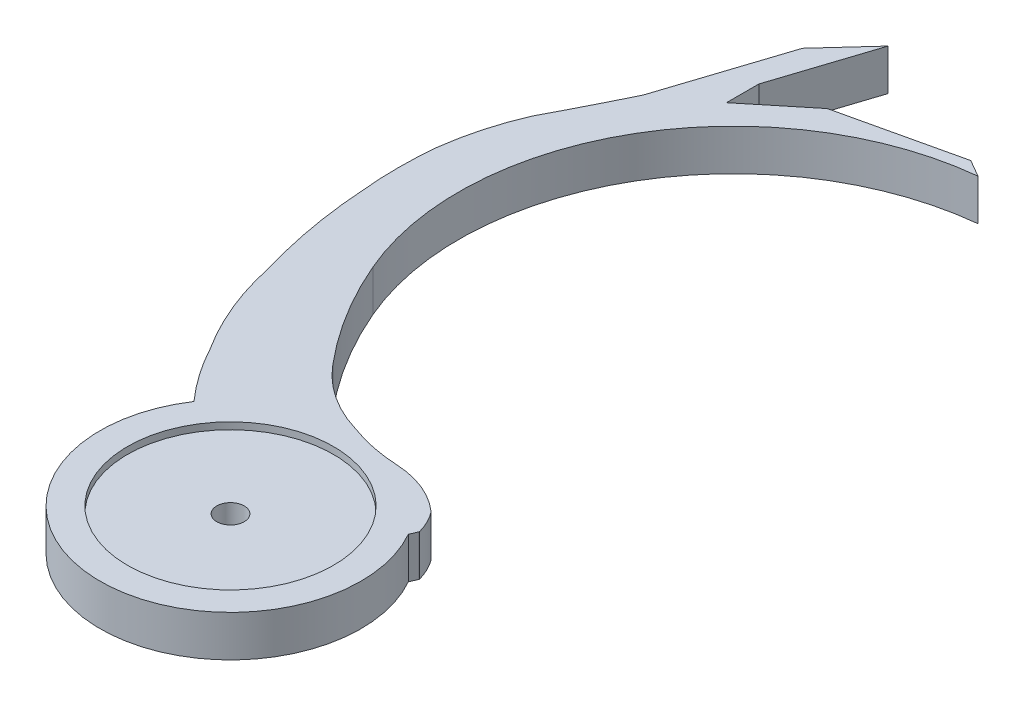
SolidWorks part; units mm, degrees
ref_plane "Front Plane" through (0, 0, 0) normal (0, 0, 1) x (1, 0, 0)
ref_plane "Top Plane" through (0, 0, 0) normal (0, 1, 0) x (1, 0, 0)
ref_plane "Right Plane" through (0, 0, 0) normal (1, 0, 0) x (0, 0, -1)
sketch "Sketch2" plane through (0, 0, 0) normal (0, 1, 0) x (1, 0, 0)
  line L0 (0, 0) -> (-35.9464, 0) construction
  line L1 (-35.9464, 0) -> (41.3976, 0) construction
  line L2 (41.3976, 0) -> (0, 0) construction
  line L3 (0, 0) -> (0, 18.7982) construction
  line L4 (0, 18.7982) -> (0, -23.465) construction
  circle A0 centre (0, 0) radius 20 construction
  circle A1 centre (0, 0) radius 23.465
sketch "Sketch4" plane through (0, 0, 0) normal (0, 1, 0) x (1, 0, 0)
  line L0 (-19.7005, -1.3216) -> (20.2972, -0.8891) construction
  circle A0 centre (0, 0) radius 23.4639 construction
  dimension "D1" = 40
sketch "Sketch5" plane through (0, 0, 0) normal (0, 1, 0) x (1, 0, 0)
  line L0 (-19.9303, -0.0851) -> (20.0695, 0.0365) construction
  dimension "D1" = 40
sketch "Sketch6" plane through (0, 0, 0) normal (0, 1, 0) x (1, 0, 0)
  line L0 (-4.3374, 0.8589) -> (-4.3374, 26.464) construction
  line L1 (-4.3374, 26.464) -> (-4.3374, -29.1693) construction
  circle A0 centre (-4.3374, 0.8589) radius 20
sketch "sungu kiri " plane through (0, 0, 0) normal (0, 1, 0) x (1, 0, 0)
  line L0 (-17.9037, 25.6768) -> (-20.2142, 18.582)
  line L1 (-20.2142, 18.582) -> (-20.2142, 16.2232)
  line L2 (-16.1729, 19.5215) -> (-7.6679, 21.4704)
  line L3 (-3.7576, -22.025) -> (-3.6458, -22.025)
  line L4 (-17.9037, 25.6768) -> (-20.8793, 22.4196)
  line L5 (-20.8793, 22.4196) -> (-23.726, 13.6785)
  line L6 (-23.3814, 7.2187) -> (-21.0655, 13.8643)
  line L8 (-21.0655, 13.8643) -> (-20.2142, 18.582)
  line L9 (-7.6679, 21.4704) -> (-6.4236, 20.7498)
  line L10 (-4.3374, 0.8589) -> (-4.3374, 13.8643) construction
  line L11 (7.4981, 19.5215) -> (11.5395, 16.2232)
  line L14 (-16.1729, 19.5215) -> (-20.2142, 16.2232)
  line L15 (-1.0069, 21.4704) -> (-2.2512, 20.7498)
  line L16 (12.3908, 13.8643) -> (11.5395, 18.582)
  line L17 (14.7066, 7.2187) -> (12.3908, 13.8643)
  line L18 (12.2046, 22.4196) -> (15.0512, 13.6785)
  line L19 (9.2289, 25.6768) -> (12.2046, 22.4196)
  line L21 (7.4981, 19.5215) -> (-1.0069, 21.4704)
  line L22 (11.5395, 18.582) -> (11.5395, 16.2232)
  line L23 (9.2289, 25.6768) -> (11.5395, 18.582)
  line L24 (-4.3374, 0.8589) -> (-4.3374, -17.8442) construction
  arc A0 (-4.3374, -21.9985) -> (-5.1555, -20.3392) centre (-9.0425, -23.287) ccw
  arc A1 (-5.1555, -20.3392) -> (-9.3619, -18.6184) centre (-9.6898, -25.4217) ccw
  arc A2 (-9.3619, -18.6184) -> (-13.1502, -17.8442) centre (-8.7528, -5.9825) cw
  arc A3 (-13.1502, -17.8442) -> (-18.7296, -13.6646) centre (-10.3234, -8.257) cw
  arc A4 (-22.7226, -7.0141) -> (-17.1413, 16.2232) centre (-4.3374, 0.8589) cw
  arc A5 (10.0549, -13.6646) -> (-4.1465, -21.4375) centre (-5.9719, -1.2427) cw construction
  arc A6 (8.4665, 16.2232) -> (-2.2512, 20.7498) centre (-4.3374, 0.8589) ccw
  arc A8 (-23.726, 13.6785) -> (-26.4444, 8.3095) centre (-176.3922, 87.6034) cw
  arc A9 (-26.4444, 8.3095) -> (-27.9369, 2.8451) centre (-7.9567, 0.3238) ccw
  arc A10 (-27.9369, 2.8451) -> (-27.9369, -2.4841) centre (-0.9166, 0.1805) ccw
  arc A11 (-27.9369, -2.4841) -> (-26.4444, -10.8627) centre (10.027, -0.0436) ccw
  arc A12 (-26.4444, -10.8627) -> (-23.4884, -18.0953) centre (-5.339, -6.4571) ccw
  arc A13 (-23.4884, -18.0953) -> (-19.0281, -23.7304) centre (-5.5688, -8.4944) ccw
  arc A14 (-19.0281, -23.7304) -> (-13.725, -28.6503) centre (23.0714, 16.3305) ccw
  arc A16 (-3.6458, -22.025) -> (-1.6826, -20.6262) centre (-3.6458, -19.9479) ccw
  arc A17 (9.1757, -14.8335) -> (14.0478, -7.0141) centre (-13.806, 4.9136) ccw
  arc A18 (-18.7296, -13.6646) -> (-5.4169, -21.3374) centre (-2.7028, -1.2427) ccw construction
  arc A19 (-17.8504, -14.8335) -> (-22.7226, -7.0141) centre (5.1312, 4.9136) cw
  circle A20 centre (-4.3374, 0.8589) radius 20 construction
  circle A21 centre (-12.8438, -27.2612) radius 9.5 construction
  arc A23 (-17.1413, 16.2232) -> (-6.4236, 20.7498) centre (-4.3374, 0.8589) cw
  arc A25 (10.3533, -23.7304) -> (5.0502, -28.6503) centre (-31.7461, 16.3305) cw
  arc A26 (14.8136, -18.0953) -> (10.3533, -23.7304) centre (-3.106, -8.4944) cw
  arc A27 (17.7696, -10.8627) -> (14.8136, -18.0953) centre (-3.3358, -6.4571) cw
  arc A28 (19.2622, -2.4841) -> (17.7696, -10.8627) centre (-18.7017, -0.0436) cw
  arc A29 (19.2622, 2.8451) -> (19.2622, -2.4841) centre (-7.7582, 0.1805) cw
  arc A30 (17.7696, 8.3095) -> (19.2622, 2.8451) centre (-0.7181, 0.3238) cw
  arc A31 (15.0512, 13.6785) -> (17.7696, 8.3095) centre (167.7174, 87.6034) ccw
  arc A32 (14.0478, -7.0141) -> (8.4665, 16.2232) centre (-4.3374, 0.8589) ccw
  arc A33 (4.4754, -17.8442) -> (10.0549, -13.6646) centre (1.6487, -8.257) ccw
  arc A34 (0.6871, -18.6184) -> (4.4754, -17.8442) centre (0.0781, -5.9825) ccw
  arc A35 (-3.5193, -20.3392) -> (0.6871, -18.6184) centre (1.015, -25.4217) cw
  arc A36 (-4.3446, -22.025) -> (-3.5193, -20.3392) centre (0.3678, -23.287) cw
  circle A37 centre (-12.8438, -27.2612) radius 7.5
  arc A38 (-8.788, -18.6705) -> (-4.5823, -22.5711) centre (-12.8438, -27.2612) ccw construction
  circle A39 centre (4.169, -27.2612) radius 7.5 construction
  circle A40 centre (4.169, -27.2612) radius 9.5 construction
  circle A41 centre (-12.8438, -27.2612) radius 1
  arc A42 (-13.725, -17.8021) -> (-4.5823, -22.5711) centre (-12.8438, -27.2612) ccw
  arc A43 (-4.3446, -22.025) -> (-4.5823, -22.5711) centre (-16.7026, -16.9703) cw
  arc A44 (-8.788, -18.6705) -> (-8.8094, -18.6604) centre (-12.8438, -27.2612) ccw
  dimension "D1" = 2
  dimension "D2" = 2
  dimension "D3" = 15
sketch "hjgjg" plane through (0, 0, 0) normal (0, 0, 1) x (1, 0, 0)
  line L0 (0, 0) -> (-35.9464, 0) construction
  line L1 (-35.9464, 0) -> (41.3976, 0) construction
  line L2 (41.3976, 0) -> (0, 0) construction
  line L3 (0, 0) -> (0, 18.7982) construction
  line L4 (0, 18.7982) -> (0, -23.465) construction
  circle A0 centre (0, 0) radius 20 construction
  circle A1 centre (0, 0) radius 23.465
extrude "Boss-Extrude1" add sketch "sungu kiri " along normal blind 3
sketch "Sketch7" plane through (0, 0, 0) normal (0, 1, 0) x (1, 0, 0)
  circle A0 centre (-12.8438, -27.2612) radius 7.5
sketch "Sketch9" plane through (0, 3, 0) normal (0, 1, 0) x (1, 0, 0)
  circle A0 centre (-12.8438, -27.2612) radius 7.5
extrude "Cut-Extrude5" cut sketch "Sketch9" against normal blind 0.5
scale "Scale1" bodies to scale 105 scale about centroid uniform scaling yes scale factor 1.75
